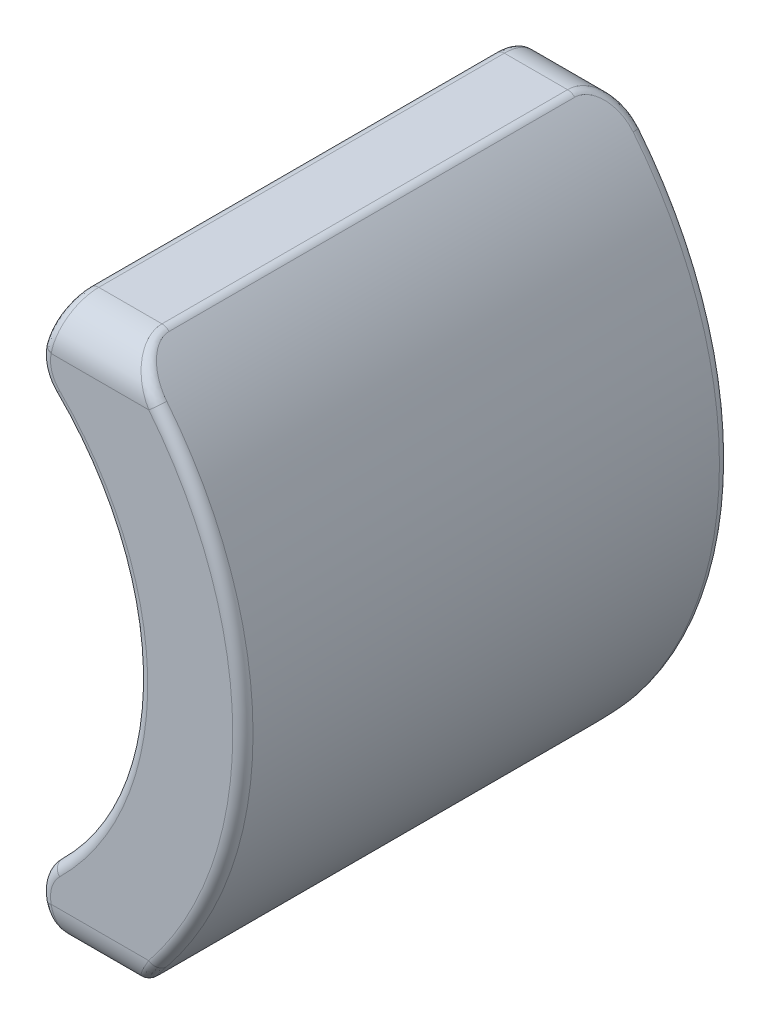
SolidWorks part; units mm, degrees
ref_plane "Front Plane" through (0, 0, 0) normal (0, 0, 1) x (1, 0, 0)
ref_plane "Top Plane" through (0, 0, 0) normal (0, 1, 0) x (1, 0, 0)
ref_plane "Right Plane" through (0, 0, 0) normal (1, 0, 0) x (0, 0, -1)
sketch "Sketch1" plane through (0, 0, 0) normal (0, 0, 1) x (1, 0, 0)
  line L0 (0, 0) -> (9.63, 0) construction
  line L1 (6.7381, -6.88) -> (4.8781, -6.88)
  line L2 (4.8781, -6.88) -> (4.5318, -5.38)
  line L3 (4.8781, 6.88) -> (4.5318, 5.38)
  line L4 (6.7381, 6.88) -> (4.8781, 6.88)
  arc A0 (6.7381, 6.88) -> (6.7381, -6.88) centre (0, 0) cw
  arc A1 (4.5318, 5.38) -> (4.5318, -5.38) centre (0, 0) cw
  point P7 (9.63, 0)
  dimension "D1" = 9.63
  dimension "D2" = 6.88
  dimension "D3" = 103
  dimension "D4" = 1.86
  dimension "D5" = 1.5
extrude "Boss-Extrude1" add sketch "Sketch1" along normal blind 12
fillet "Fillet1" radius 1 2 edges at (4.5318, 5.38, 6) (4.5318, -5.38, 6)
fillet "Fillet2" radius 1 4 edges at (5.8081, -6.88, 0) (5.8081, -6.88, 12) (5.8081, 6.88, 12) (5.8081, 6.88, 0)
fillet "Fillet3" radius 0.25 24 edges at (6.9882, -6.6258, 11.6661) (6.7381, -6.88, 6) (6.8685, -6.7498, 0.5066) (9.63, 0, 0) (6.9882, 6.6258, 0.3339) (6.7381, 6.88, 6) (6.8685, 6.7498, 11.4934) (4.8161, 6.6112, 11.6822) (4.8781, 6.88, 6) (4.8161, 6.6112, 0.3178) (4.6879, 5.4113, 0) (7.0343, 0, 0) (4.6879, -5.4113, 0) (4.8161, -6.6112, 0.3178) (4.8781, -6.88, 6) (4.8161, -6.6112, 11.6822) (7.0343, 0, 12) (4.6879, 5.4113, 12) (9.63, 0, 12) (4.6879, -5.4113, 12)
